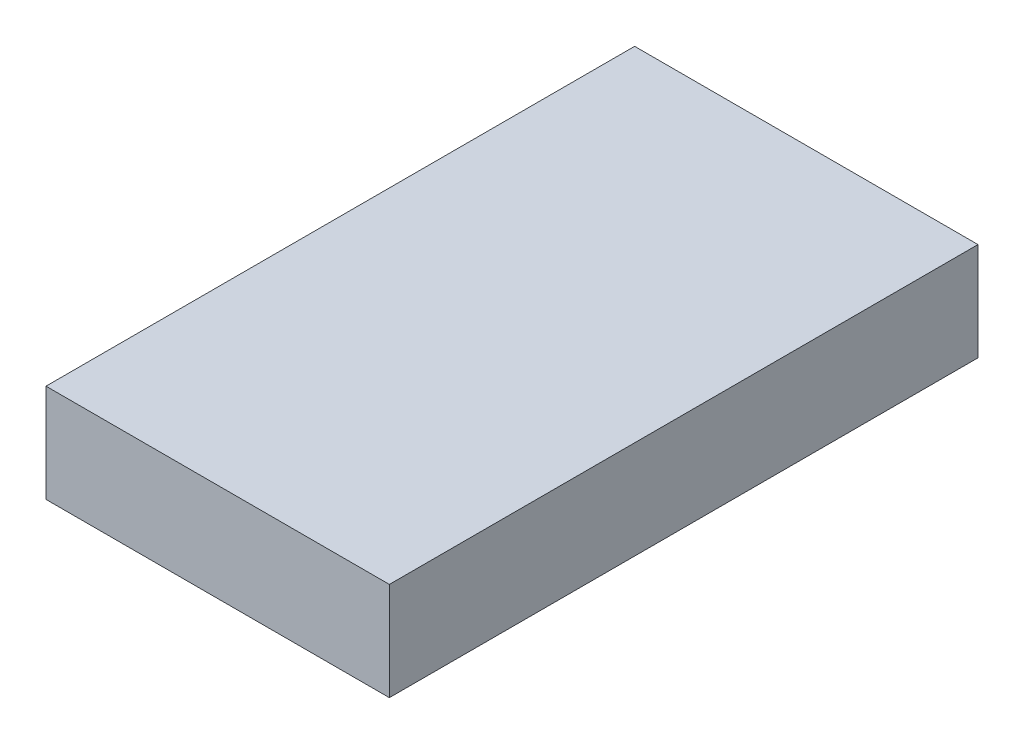
SolidWorks part; units mm, degrees
ref_plane "前视基准面" through (0, 0, 0) normal (0, 0, 1) x (1, 0, 0)
ref_plane "上视基准面" through (0, 0, 0) normal (0, 1, 0) x (1, 0, 0)
ref_plane "右视基准面" through (0, 0, 0) normal (1, 0, 0) x (0, 0, -1)
other "Configuration Table"
sketch "草图1" plane through (0, 0, 0) normal (0, 1, 0) x (1, 0, 0)
  line L1 (0, 0) -> (7, 0)
  line L2 (0, 0) -> (0, 12)
  line L3 (0, 12) -> (7, 12)
  line L4 (7, 0) -> (7, 12)
  line L5 (0, 0) -> (7, 12) construction
  line L6 (0, 12) -> (7, 0) construction
  point P4 (3.5, 6)
  dimension "D1" = 7
  dimension "D2" = 12
extrude "凸台-拉伸1" add sketch "草图1" along normal blind 2
